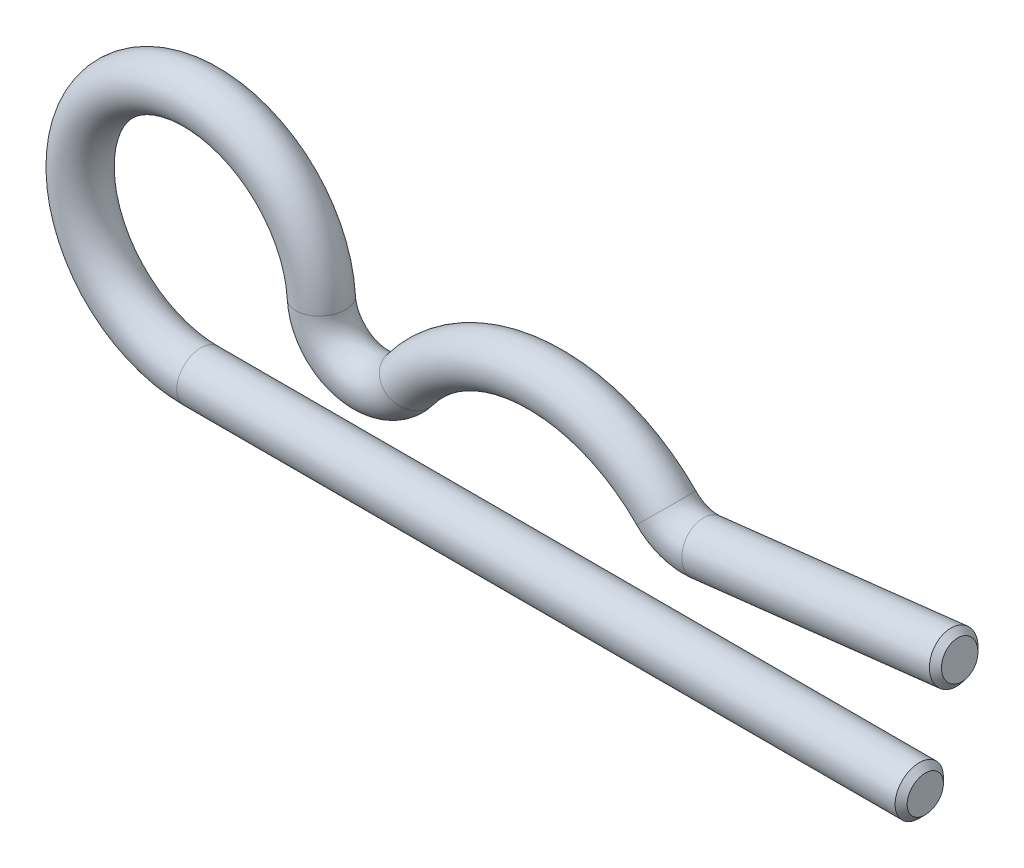
SolidWorks part; units mm, degrees
material "AISI 4340 Steel, annealed"
ref_plane "Front Plane" through (0, 0, 0) normal (0, 0, 1) x (1, 0, 0)
ref_plane "Top Plane" through (0, 0, 0) normal (0, 1, 0) x (1, 0, 0)
ref_plane "Right Plane" through (0, 0, 0) normal (1, 0, 0) x (0, 0, -1)
sketch "Sketch1" plane through (0, 0, 0) normal (0, 0, 1) x (1, 0, 0)
  line L0 (5, 0) -> (-25, 0)
  line L1 (-16.3279, 4.196) -> (-5.1219, 4.196) construction
  line L2 (-4.0728, 4.3164) -> (6.4272, 5.5217)
  arc A0 (-20.009, 5.3) -> (-25, 0) centre (-25, 5) ccw
  arc A1 (-20.009, 5.3) -> (-16.3279, 4.196) centre (-17.9661, 5.4228) ccw
  arc A2 (-5.7284, 4.9026) -> (-16.3279, 4.196) centre (-10.7249, 0) ccw
  arc A3 (-5.7284, 4.9026) -> (-4.0728, 4.3164) centre (-4.3009, 6.3034) ccw
  dimension "D1" = 30
  dimension "D2" = 10
  dimension "D3" = 14
  dimension "D7" = 2
  dimension "D6" = 0.3
sweep "Sweep1" add path "Sketch1" circular profile diameter 2 parameters "D3"=2
chamfer "Chamfer1" distance 0.25 angle 45 2 edges at (6.3132, 6.5152, 0) (5, -1, 0)
